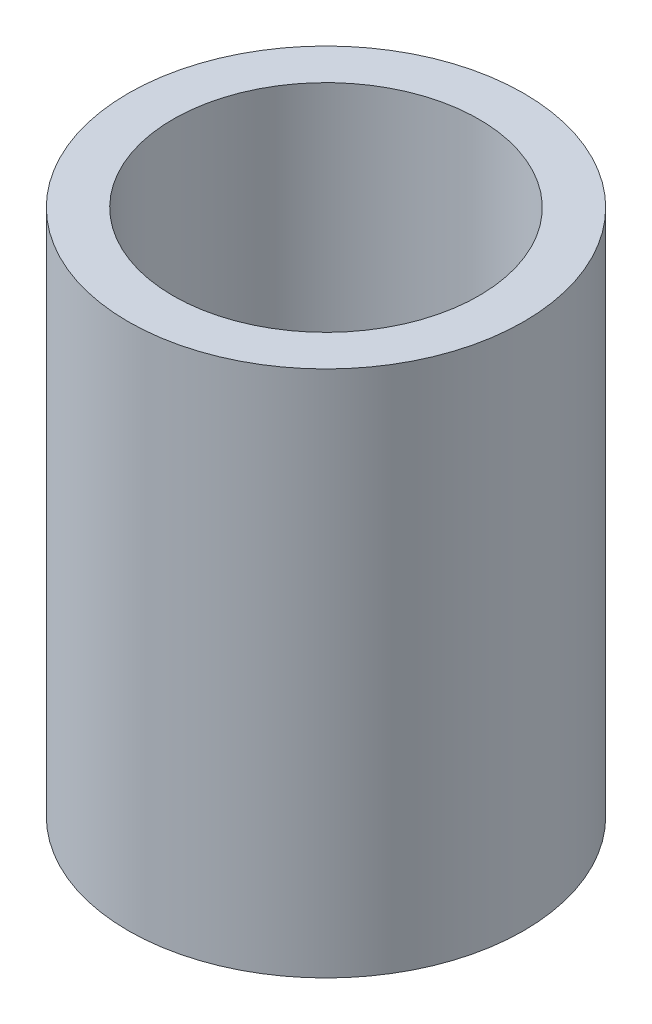
SolidWorks part; units mm, degrees
material "2024 Alloy"
ref_plane "Front Plane" through (0, 0, 0) normal (0, 0, 1) x (1, 0, 0)
ref_plane "Top Plane" through (0, 0, 0) normal (0, 1, 0) x (1, 0, 0)
ref_plane "Right Plane" through (0, 0, 0) normal (1, 0, 0) x (0, 0, -1)
sketch "Sketch1" plane through (0, 0, 0) normal (0, 1, 0) x (1, 0, 0)
  circle A0 centre (0, 0) radius 1.905
  dimension "D1" = 3.81
extrude "Boss-Extrude1" add sketch "Sketch1" along normal blind 5.08
hole_wizard "#4 Clearance Hole1" positions "Sketch3" profile "Sketch2" hole size "#4" standard "ANSI Inch" end condition through all
sketch "Sketch3" plane through (0, 5.08, 0) normal (0, 1, 0) x (1, 0, 0)
  point P0 (0, 0)
sketch "Sketch2" plane through (0, 5.08, 0) normal (1, 0, 0) x (0, 0, 1)
  line L0 (0, 0) -> (0, 5.08)
  line L1 (0, 5.08) -> (1.4732, 5.08)
  line L2 (1.4732, 5.08) -> (1.4732, 0)
  line L5 (1.4732, 0) -> (0, 0)
  line L11 (0, -6.35) -> (0, 107.95) construction
  dimension "Thru Hole Dia." = 2.9464
  dimension "Thru Hole Depth" = 5.08
